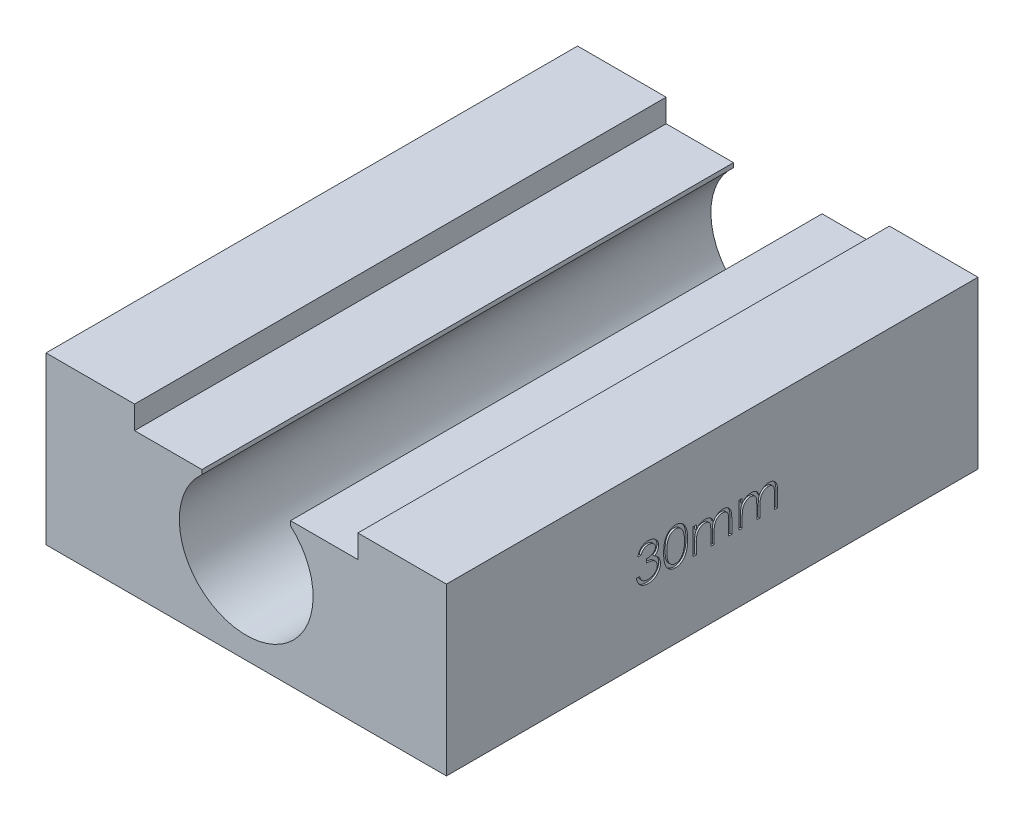
SolidWorks part; units mm, degrees
ref_plane "Front Plane" through (0, 0, 0) normal (0, 0, 1) x (1, 0, 0)
ref_plane "Top Plane" through (0, 0, 0) normal (0, 1, 0) x (1, 0, 0)
ref_plane "Right Plane" through (0, 0, 0) normal (1, 0, 0) x (0, 0, -1)
sketch "Sketch1" plane through (0, 0, 0) normal (0, 0, 1) x (1, 0, 0)
  line L0 (0, 0) -> (0, 22.5142) construction
  line L1 (0, 22.5142) -> (-10, 12.5142)
  line L2 (0, 22.5142) -> (10, 12.5142)
  line L3 (-10, 12.5142) -> (-25, 12.5142)
  line L4 (-25, 12.5142) -> (-25, 32.5142)
  line L5 (-25, 32.5142) -> (25, 32.5142)
  line L6 (25, 32.5142) -> (25, 12.5142)
  line L7 (25, 12.5142) -> (10, 12.5142)
  line L8 (-45.2, 17.5142) -> (-45.2, -20)
  line L9 (-45.2, -20) -> (45.2, -20)
  line L10 (45.2, -20) -> (45.2, 17.5142)
  line L11 (45.2, 17.5142) -> (25.2, 17.5142)
  line L12 (25.2, 17.5142) -> (25.2, 12.3142)
  line L13 (-25.2, 12.3142) -> (-10, 12.3142)
  line L14 (-45.2, 17.5142) -> (-25.2, 17.5142)
  line L15 (-25.2, 17.5142) -> (-25.2, 12.3142)
  line L16 (25.2, 12.3142) -> (10, 12.3142)
  line L17 (-10, 12.3142) -> (-10, 11.3142)
  line L18 (10, 12.3142) -> (10, 11.3142)
  circle A0 centre (0, 0) radius 15.1
  dimension "D12" = 30.2
  dimension "D1" = 45
  dimension "D2" = 10
  dimension "D3" = 20
  dimension "D4" = 50
  dimension "D5" = 25
  dimension "D6" = 5
  dimension "D7" = 0.2
  dimension "D8" = 0.2
  dimension "D9" = 5
  dimension "D10" = 20
  dimension "D11" = 20
  dimension "D13" = 20
  dimension "D14" = 0.2
  dimension "D15" = 0.2
  dimension "D16" = 1
extrude "Boss-Extrude1" add sketch "Sketch1" along normal blind 120 contours A0 L17 L13 L15 L14 L8 L9 L10 L11 L12 L16 L18
sketch "Sketch2" plane through (45.2, 0, 0) normal (1, 0, 0) x (0, 0, -1)
  text T0 "30mm" font "Century Gothic" height 8
extrude "Cut-Extrude1" cut sketch "Sketch2" against normal blind 0.4
